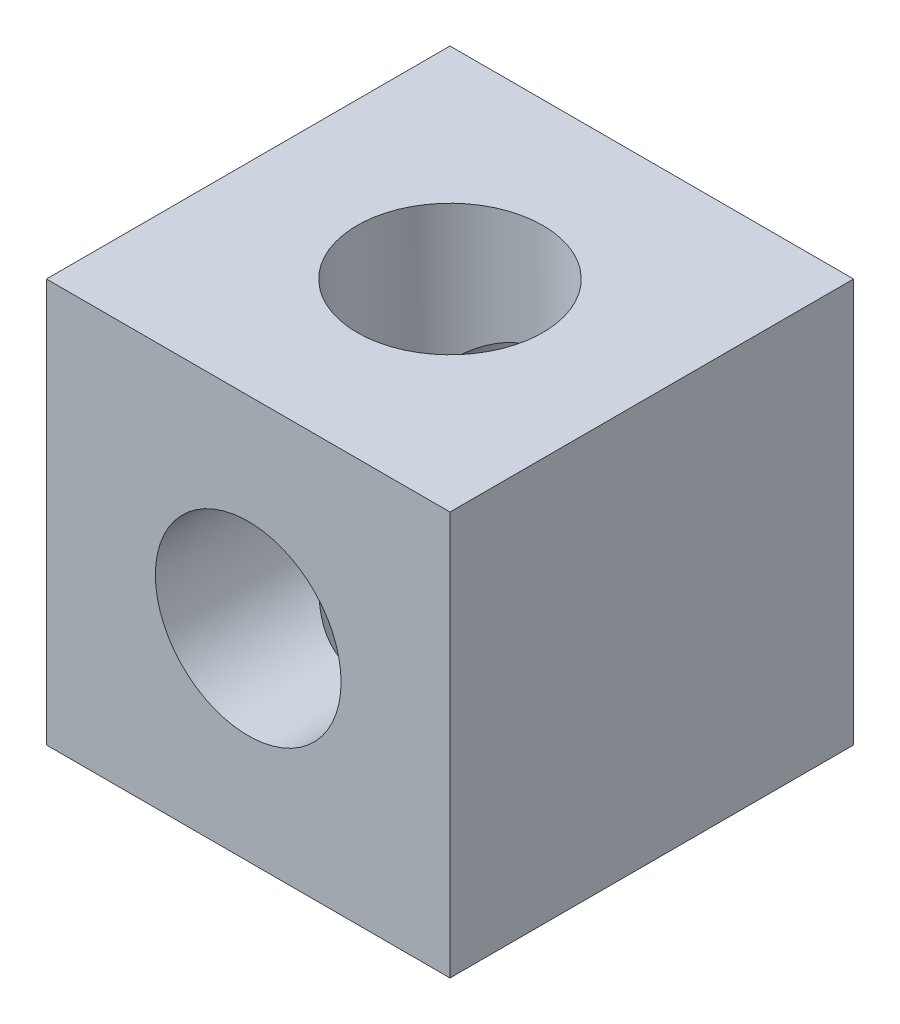
SolidWorks part; units mm, degrees
ref_plane "Front Plane" through (0, 0, 0) normal (0, 0, 1) x (1, 0, 0)
ref_plane "Top Plane" through (0, 0, 0) normal (0, 1, 0) x (1, 0, 0)
ref_plane "Right Plane" through (0, 0, 0) normal (1, 0, 0) x (0, 0, -1)
sketch "Sketch1" plane through (0, 0, 0) normal (0, 1, 0) x (1, 0, 0)
  line L1 (-10.16, -10.16) -> (10.16, -10.16)
  line L2 (-10.16, -10.16) -> (-10.16, 10.16)
  line L3 (-10.16, 10.16) -> (10.16, 10.16)
  line L4 (10.16, -10.16) -> (10.16, 10.16)
  line L5 (-10.16, -10.16) -> (10.16, 10.16) construction
  line L6 (-10.16, 10.16) -> (10.16, -10.16) construction
  point P0 (0, 0)
  dimension "D1" = 20.32
extrude "Boss-Extrude1" add sketch "Sketch1" along normal mid plane 20.32
sketch "Sketch2" plane through (0, 0, 10.16) normal (0, 0, 1) x (1, 0, 0)
  circle A0 centre (0, 0) radius 4.675
  dimension "D1" = 9.35
extrude "Cut-Extrude1" cut sketch "Sketch2" against normal up to next
sketch "Sketch3" plane through (0, 10.16, 0) normal (0, 1, 0) x (1, 0, 0)
  circle A0 centre (0, 0) radius 4.675
  dimension "D1" = 9.35
extrude "Cut-Extrude2" cut sketch "Sketch3" against normal through all
